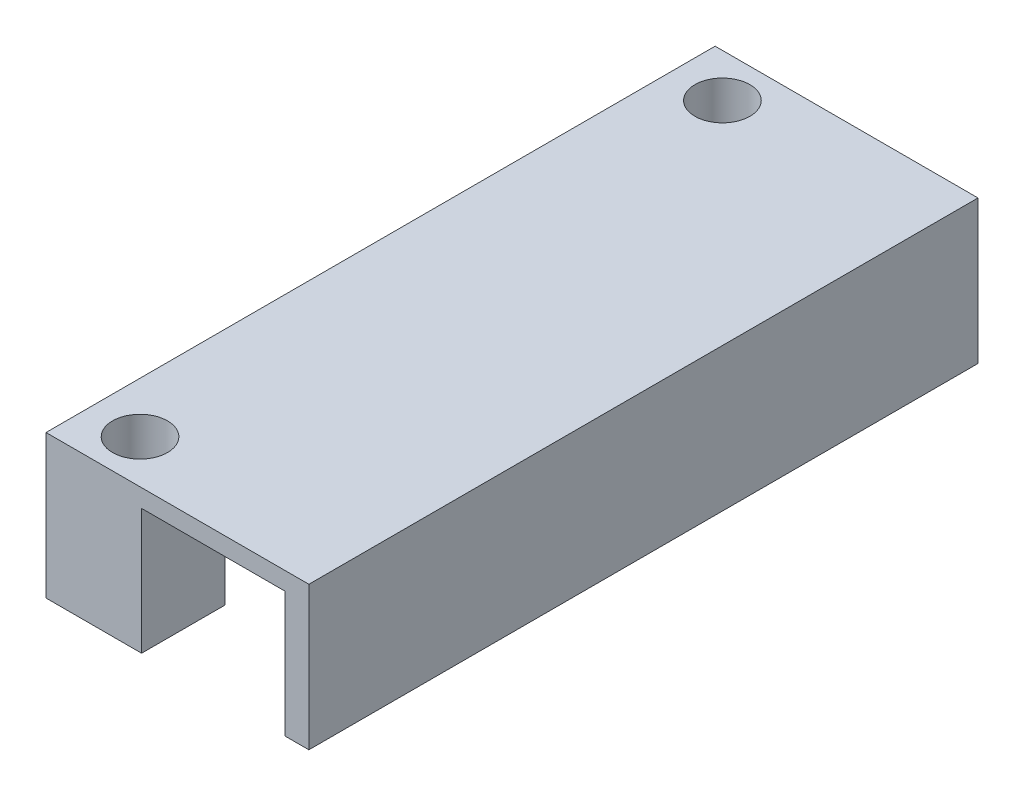
SolidWorks part; units mm, degrees
ref_plane "Front Plane" through (0, 0, 0) normal (0, 0, 1) x (1, 0, 0)
ref_plane "Top Plane" through (0, 0, 0) normal (0, 1, 0) x (1, 0, 0)
ref_plane "Right Plane" through (0, 0, 0) normal (1, 0, 0) x (0, 0, -1)
sketch "Sketch1" plane through (0, 0, 0) normal (0, 1, 0) x (1, 0, 0)
  line L0 (0, 27) -> (0, -20) construction
  line L1 (-10, -20) -> (10, -20) construction
  line L2 (-10, -20) -> (-10, 20)
  line L3 (-10, 20) -> (10, 20) construction
  line L4 (10, -20) -> (10, 20) construction
  line L5 (-10, -20) -> (10, 20) construction
  line L6 (-10, 20) -> (10, -20) construction
  line L7 (-10, 20) -> (10, 20) construction
  line L8 (-10, 20) -> (-10, 27)
  line L9 (-10, 27) -> (10, 27)
  line L10 (10, 20) -> (10, 27) construction
  line L11 (-10, 0) -> (10, 0) construction
  line L12 (10, -20) -> (10, -27) construction
  line L13 (-10, -20) -> (-10, -27)
  line L14 (-10, -27) -> (10, -27)
  line L16 (10, 27) -> (12, 27)
  line L17 (10, 27) -> (10, -27) construction
  line L18 (10, -27) -> (12, -27)
  line L19 (12, 27) -> (12, -27)
  circle A0 centre (-5.76, 24.37) radius 2.3
  circle A1 centre (5.76, 24.37) radius 2.3 construction
  circle A2 centre (5.76, -24.37) radius 2.3 construction
  circle A3 centre (-5.76, -24.37) radius 2.3
  circle A4 centre (0, 0) radius 5.35 construction
  point P0 (0, 0)
  dimension "D4" = 4.24
  dimension "D6" = 4.6
  dimension "D8" = 10.7
  dimension "D1" = 40
  dimension "D2" = 20
  dimension "D3" = 7
  dimension "D5" = 2.63
  dimension "D7" = 2
  dimension "D9" = 54
extrude "Boss-Extrude2" add sketch "Sketch1" along normal blind 12 contours L19 L16 L9 L8 L2 L13 L14 L18 A0 A3
sketch "Sketch3" plane through (0, 0, 0) normal (0, -1, 0) x (1, 0, 0)
  line L0 (-10, 27) -> (12, 27) construction
  line L1 (10, 27) -> (-2, 27)
  line L2 (10, 27) -> (10, -27)
  line L3 (10, -27) -> (-2, -27)
  line L4 (-2, 27) -> (-2, 21)
  line L5 (-10, -27) -> (12, -27) construction
  line L6 (12, -27) -> (12, 27) construction
  line L7 (-2, -21) -> (-2, -27)
  line L8 (-2, 21) -> (-10, 21)
  line L10 (-2, -21) -> (-10, -21)
  line L11 (-10, 21) -> (-10, -21)
  dimension "D1" = 2
  dimension "D2" = 12
  dimension "D3" = 42
  dimension "D4" = 21
  dimension "D5" = 8
extrude "Cut-Extrude1" cut sketch "Sketch3" against normal blind 10.5
sketch "Sketch4" plane through (0, 10.5, 0) normal (0, -1, 0) x (1, 0, 0)
  line L0 (-10, 0) -> (12, 0) construction
  line L1 (-10, 27) -> (12, 27)
  line L2 (-10, 27) -> (-10, 28)
  line L3 (-10, 28) -> (12, 28)
  line L4 (12, 27) -> (12, 28)
  line L5 (-10, 21) -> (-10, -21) construction
  line L6 (12, -27) -> (12, 27) construction
  line L7 (-10, -28) -> (12, -28)
  line L8 (12, -27) -> (12, -28)
  line L9 (-10, -27) -> (12, -27)
  line L10 (-10, -27) -> (-10, -28)
  dimension "D1" = 1
extrude "Boss-Extrude3" add sketch "Sketch4" along normal up to surface (12 mm away) from surface at -1.5 up to face at (-6, 0, 24) starting at face at (1, 12, 0)
sketch "Sketch5" plane through (0, 10.5, 0) normal (0, -1, 0) x (1, 0, 0)
  line L0 (12, 28) -> (-10, 28) construction
  line L1 (-2, 28) -> (10, 28)
  line L2 (-2, 28) -> (-2, -28)
  line L3 (-2, -28) -> (10, -28)
  line L4 (10, 28) -> (10, -28)
  line L5 (-10, -28) -> (12, -28) construction
  line L6 (10, -27) -> (10, 27) construction
  dimension "D1" = 0
extrude "Cut-Extrude2" cut sketch "Sketch5" along normal up to surface (10.5 mm away) from surface at 0 up to face at (-0.3333, 0, 0) starting at face at (-1, 10.5, 0)
